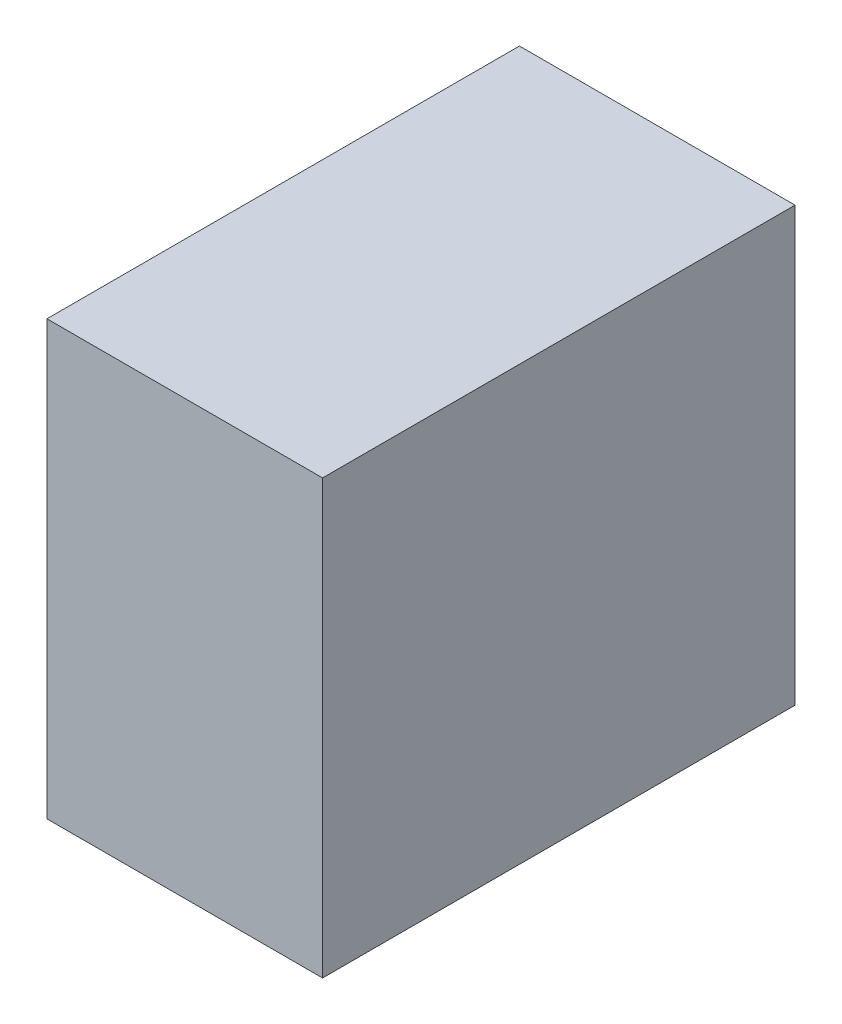
SolidWorks part; units mm, degrees
ref_plane "Front Plane" through (0, 0, 0) normal (0, 0, 1) x (1, 0, 0)
ref_plane "Top Plane" through (0, 0, 0) normal (0, 1, 0) x (1, 0, 0)
ref_plane "Right Plane" through (0, 0, 0) normal (1, 0, 0) x (0, 0, -1)
sketch "Sketch1" plane through (0, 0, 0) normal (0, 0, 1) x (1, 0, 0)
  line L1 (88.9, -139.7) -> (-88.9, -139.7)
  line L2 (88.9, -139.7) -> (88.9, 139.7)
  line L3 (88.9, 139.7) -> (-88.9, 139.7)
  line L4 (-88.9, -139.7) -> (-88.9, 139.7)
  line L5 (88.9, -139.7) -> (-88.9, 139.7) construction
  line L6 (88.9, 139.7) -> (-88.9, -139.7) construction
  point P0 (0, 0)
  dimension "D1" = 279.4
  dimension "D2" = 177.8
extrude "Boss-Extrude1" add sketch "Sketch1" along normal blind 304.8
